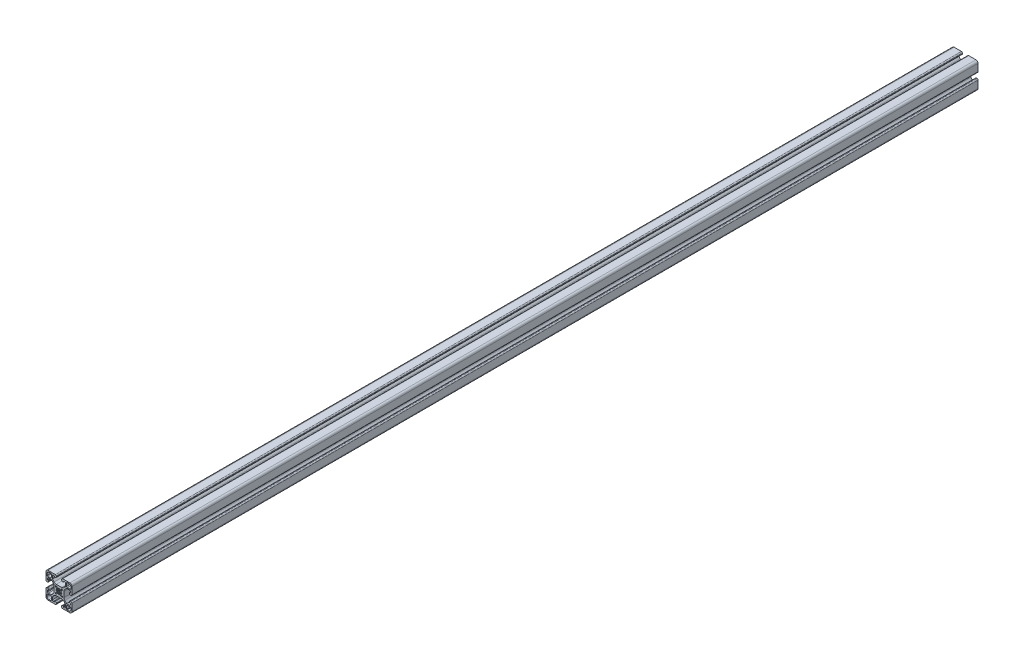
SolidWorks part; units mm, degrees
other "Extrude1"
material "6105-T5 Aluminum"
ref_plane "Front Plane" through (0, 0, 0) normal (0, 0, 1) x (1, 0, 0)
ref_plane "Top Plane" through (0, 0, 0) normal (0, 1, 0) x (1, 0, 0)
ref_plane "Right Plane" through (0, 0, 0) normal (1, 0, 0) x (0, 0, -1)
sketch "Sketch1" plane through (0, 0, 0) normal (0, 0, 1) x (1, 0, 0)
  line L0 (12.4898, -18.345) -> (15.545, -18.345)
  line L1 (11.8598, -13.1298) -> (11.8598, -17.715)
  line L2 (17.715, -11.8598) -> (13.1298, -11.8598)
  line L3 (18.345, -15.545) -> (18.345, -12.4898)
  line L4 (-18.345, -12.4898) -> (-18.345, -15.545)
  line L5 (-13.1298, -11.8598) -> (-17.715, -11.8598)
  line L6 (-11.8598, -17.715) -> (-11.8598, -13.1298)
  line L7 (-15.545, -18.345) -> (-12.4898, -18.345)
  line L8 (18.345, 12.4898) -> (18.345, 15.545)
  line L9 (13.1298, 11.8598) -> (17.715, 11.8598)
  line L10 (11.8598, 17.715) -> (11.8598, 13.1298)
  line L11 (15.545, 18.345) -> (12.4898, 18.345)
  line L12 (-12.4898, 18.345) -> (-15.545, 18.345)
  line L13 (-11.8598, 13.1298) -> (-11.8598, 17.715)
  line L14 (-17.715, 11.8598) -> (-13.1298, 11.8598)
  line L15 (-18.345, 15.545) -> (-18.345, 12.4898)
  line L16 (-5.63, 20) -> (-16.83, 20)
  line L17 (-20, 16.83) -> (-20, 5.63)
  line L18 (-18.43, 4.06) -> (-17.57, 4.06)
  line L19 (-16, 5.63) -> (-16, 6.605)
  line L20 (-16.25, 6.855) -> (-17.25, 6.855)
  line L21 (-17.5, 7.105) -> (-17.5, 9.015)
  line L22 (-16.23, 10.285) -> (-12.2162, 10.285)
  line L23 (-11.5869, 10.0243) -> (-9.0762, 7.5137)
  line L24 (-7.685, 4.1549) -> (-7.685, -4.1549)
  line L25 (-9.0762, -7.5137) -> (-11.5869, -10.0243)
  line L26 (-12.2162, -10.285) -> (-16.23, -10.285)
  line L27 (-17.5, -9.015) -> (-17.5, -7.105)
  line L28 (-17.25, -6.855) -> (-16.25, -6.855)
  line L29 (-16, -6.605) -> (-16, -5.63)
  line L30 (-17.57, -4.06) -> (-18.43, -4.06)
  line L31 (-20, -5.63) -> (-20, -16.83)
  line L32 (-16.83, -20) -> (-5.63, -20)
  line L33 (-4.06, -18.43) -> (-4.06, -17.57)
  line L34 (-5.63, -16) -> (-6.605, -16)
  line L35 (-6.855, -16.25) -> (-6.855, -17.25)
  line L36 (-7.105, -17.5) -> (-9.015, -17.5)
  line L37 (-10.285, -16.23) -> (-10.285, -12.2162)
  line L38 (-10.0243, -11.5869) -> (-7.5137, -9.0762)
  line L39 (-4.1549, -7.685) -> (4.1549, -7.685)
  line L40 (7.5137, -9.0762) -> (10.0243, -11.5869)
  line L41 (10.285, -12.2162) -> (10.285, -16.23)
  line L42 (9.015, -17.5) -> (7.105, -17.5)
  line L43 (6.855, -17.25) -> (6.855, -16.25)
  line L44 (6.605, -16) -> (5.63, -16)
  line L45 (4.06, -17.57) -> (4.06, -18.43)
  line L46 (5.63, -20) -> (16.83, -20)
  line L47 (20, -16.83) -> (20, -5.63)
  line L48 (18.43, -4.06) -> (17.57, -4.06)
  line L49 (16, -5.63) -> (16, -6.605)
  line L50 (16.25, -6.855) -> (17.25, -6.855)
  line L51 (17.5, -7.105) -> (17.5, -9.015)
  line L52 (16.23, -10.285) -> (12.2162, -10.285)
  line L53 (11.5869, -10.0243) -> (9.0762, -7.5137)
  line L54 (7.685, -4.1549) -> (7.685, 4.1549)
  line L55 (9.0762, 7.5137) -> (11.5869, 10.0243)
  line L56 (12.2162, 10.285) -> (16.23, 10.285)
  line L57 (17.5, 9.015) -> (17.5, 7.105)
  line L58 (17.25, 6.855) -> (16.25, 6.855)
  line L59 (16, 6.605) -> (16, 5.63)
  line L60 (17.57, 4.06) -> (18.43, 4.06)
  line L61 (20, 5.63) -> (20, 16.83)
  line L62 (16.83, 20) -> (5.63, 20)
  line L63 (4.06, 18.43) -> (4.06, 17.57)
  line L64 (5.63, 16) -> (6.605, 16)
  line L65 (6.855, 16.25) -> (6.855, 17.25)
  line L66 (7.105, 17.5) -> (9.015, 17.5)
  line L67 (10.285, 16.23) -> (10.285, 12.2162)
  line L68 (10.0243, 11.5869) -> (7.5137, 9.0762)
  line L69 (4.1549, 7.685) -> (-4.1549, 7.685)
  line L70 (-7.5137, 9.0762) -> (-10.0243, 11.5869)
  line L71 (-10.285, 12.2162) -> (-10.285, 16.23)
  line L72 (-9.015, 17.5) -> (-7.105, 17.5)
  line L73 (-6.855, 17.25) -> (-6.855, 16.25)
  line L74 (-6.605, 16) -> (-5.63, 16)
  line L75 (-4.06, 17.57) -> (-4.06, 18.43)
  line L76 (-4.8481, -5.4393) -> (-3.712, -5.1263)
  line L77 (-3.712, -5.1263) -> (-1.5907, -3.0049)
  line L78 (-0.625, -3.3421) -> (-0.4923, -4.0876)
  line L79 (0.4923, -4.0876) -> (0.625, -3.3421)
  line L80 (1.5907, -3.0049) -> (3.712, -5.1263)
  line L81 (3.712, -5.1263) -> (4.8481, -5.4393)
  line L82 (5.4393, -4.8481) -> (5.1263, -3.712)
  line L83 (5.1263, -3.712) -> (3.0049, -1.5907)
  line L84 (3.3421, -0.625) -> (4.0876, -0.4923)
  line L85 (4.0876, 0.4923) -> (3.3421, 0.625)
  line L86 (3.0049, 1.5907) -> (5.1263, 3.712)
  line L87 (5.1263, 3.712) -> (5.4393, 4.8481)
  line L88 (4.8481, 5.4393) -> (3.712, 5.1263)
  line L89 (3.712, 5.1263) -> (1.5907, 3.0049)
  line L90 (0.625, 3.3421) -> (0.4923, 4.0876)
  line L91 (-0.4923, 4.0876) -> (-0.625, 3.3421)
  line L92 (-1.5907, 3.0049) -> (-3.712, 5.1263)
  line L93 (-3.712, 5.1263) -> (-4.8481, 5.4393)
  line L94 (-5.4393, 4.8481) -> (-5.1263, 3.712)
  line L95 (-5.1263, 3.712) -> (-3.0049, 1.5907)
  line L96 (-3.3421, 0.625) -> (-4.0876, 0.4923)
  line L97 (-4.0876, -0.4923) -> (-3.3421, -0.625)
  line L98 (-3.0049, -1.5907) -> (-5.1263, -3.712)
  line L99 (-5.1263, -3.712) -> (-5.4393, -4.8481)
  arc A0 (15.545, -18.345) -> (18.345, -15.545) centre (15.545, -15.545) ccw
  arc A1 (11.8598, -17.715) -> (12.4898, -18.345) centre (12.4898, -17.715) ccw
  arc A2 (13.1298, -11.8598) -> (11.8598, -13.1298) centre (13.1298, -13.1298) ccw
  arc A3 (18.345, -12.4898) -> (17.715, -11.8598) centre (17.715, -12.4898) ccw
  arc A4 (-18.345, -15.545) -> (-15.545, -18.345) centre (-15.545, -15.545) ccw
  arc A5 (-17.715, -11.8598) -> (-18.345, -12.4898) centre (-17.715, -12.4898) ccw
  arc A6 (-11.8598, -13.1298) -> (-13.1298, -11.8598) centre (-13.1298, -13.1298) ccw
  arc A7 (-12.4898, -18.345) -> (-11.8598, -17.715) centre (-12.4898, -17.715) ccw
  arc A8 (18.345, 15.545) -> (15.545, 18.345) centre (15.545, 15.545) ccw
  arc A9 (17.715, 11.8598) -> (18.345, 12.4898) centre (17.715, 12.4898) ccw
  arc A10 (11.8598, 13.1298) -> (13.1298, 11.8598) centre (13.1298, 13.1298) ccw
  arc A11 (12.4898, 18.345) -> (11.8598, 17.715) centre (12.4898, 17.715) ccw
  arc A12 (-15.545, 18.345) -> (-18.345, 15.545) centre (-15.545, 15.545) ccw
  arc A13 (-11.8598, 17.715) -> (-12.4898, 18.345) centre (-12.4898, 17.715) ccw
  arc A14 (-13.1298, 11.8598) -> (-11.8598, 13.1298) centre (-13.1298, 13.1298) ccw
  arc A15 (-18.345, 12.4898) -> (-17.715, 11.8598) centre (-17.715, 12.4898) ccw
  arc A16 (-4.06, 18.43) -> (-5.63, 20) centre (-5.63, 18.43) ccw
  arc A17 (-16.83, 20) -> (-20, 16.83) centre (-16.83, 16.83) ccw
  arc A18 (-20, 5.63) -> (-18.43, 4.06) centre (-18.43, 5.63) ccw
  arc A19 (-17.57, 4.06) -> (-16, 5.63) centre (-17.57, 5.63) ccw
  arc A20 (-16, 6.605) -> (-16.25, 6.855) centre (-16.25, 6.605) ccw
  arc A21 (-17.5, 7.105) -> (-17.25, 6.855) centre (-17.25, 7.105) ccw
  arc A22 (-16.23, 10.285) -> (-17.5, 9.015) centre (-16.23, 9.015) ccw
  arc A23 (-11.5869, 10.0243) -> (-12.2162, 10.285) centre (-12.2162, 9.395) ccw
  arc A24 (-7.685, 4.1549) -> (-9.0762, 7.5137) centre (-12.435, 4.1549) ccw
  arc A25 (-9.0762, -7.5137) -> (-7.685, -4.1549) centre (-12.435, -4.1549) ccw
  arc A26 (-12.2162, -10.285) -> (-11.5869, -10.0243) centre (-12.2162, -9.395) ccw
  arc A27 (-17.5, -9.015) -> (-16.23, -10.285) centre (-16.23, -9.015) ccw
  arc A28 (-17.25, -6.855) -> (-17.5, -7.105) centre (-17.25, -7.105) ccw
  arc A29 (-16.25, -6.855) -> (-16, -6.605) centre (-16.25, -6.605) ccw
  arc A30 (-16, -5.63) -> (-17.57, -4.06) centre (-17.57, -5.63) ccw
  arc A31 (-18.43, -4.06) -> (-20, -5.63) centre (-18.43, -5.63) ccw
  arc A32 (-20, -16.83) -> (-16.83, -20) centre (-16.83, -16.83) ccw
  arc A33 (-5.63, -20) -> (-4.06, -18.43) centre (-5.63, -18.43) ccw
  arc A34 (-4.06, -17.57) -> (-5.63, -16) centre (-5.63, -17.57) ccw
  arc A35 (-6.605, -16) -> (-6.855, -16.25) centre (-6.605, -16.25) ccw
  arc A36 (-7.105, -17.5) -> (-6.855, -17.25) centre (-7.105, -17.25) ccw
  arc A37 (-10.285, -16.23) -> (-9.015, -17.5) centre (-9.015, -16.23) ccw
  arc A38 (-10.0243, -11.5869) -> (-10.285, -12.2162) centre (-9.395, -12.2162) ccw
  arc A39 (-4.1549, -7.685) -> (-7.5137, -9.0762) centre (-4.1549, -12.435) ccw
  arc A40 (7.5137, -9.0762) -> (4.1549, -7.685) centre (4.1549, -12.435) ccw
  arc A41 (10.285, -12.2162) -> (10.0243, -11.5869) centre (9.395, -12.2162) ccw
  arc A42 (9.015, -17.5) -> (10.285, -16.23) centre (9.015, -16.23) ccw
  arc A43 (6.855, -17.25) -> (7.105, -17.5) centre (7.105, -17.25) ccw
  arc A44 (6.855, -16.25) -> (6.605, -16) centre (6.605, -16.25) ccw
  arc A45 (5.63, -16) -> (4.06, -17.57) centre (5.63, -17.57) ccw
  arc A46 (4.06, -18.43) -> (5.63, -20) centre (5.63, -18.43) ccw
  arc A47 (16.83, -20) -> (20, -16.83) centre (16.83, -16.83) ccw
  arc A48 (20, -5.63) -> (18.43, -4.06) centre (18.43, -5.63) ccw
  arc A49 (17.57, -4.06) -> (16, -5.63) centre (17.57, -5.63) ccw
  arc A50 (16, -6.605) -> (16.25, -6.855) centre (16.25, -6.605) ccw
  arc A51 (17.5, -7.105) -> (17.25, -6.855) centre (17.25, -7.105) ccw
  arc A52 (16.23, -10.285) -> (17.5, -9.015) centre (16.23, -9.015) ccw
  arc A53 (11.5869, -10.0243) -> (12.2162, -10.285) centre (12.2162, -9.395) ccw
  arc A54 (7.685, -4.1549) -> (9.0762, -7.5137) centre (12.435, -4.1549) ccw
  arc A55 (9.0762, 7.5137) -> (7.685, 4.1549) centre (12.435, 4.1549) ccw
  arc A56 (12.2162, 10.285) -> (11.5869, 10.0243) centre (12.2162, 9.395) ccw
  arc A57 (17.5, 9.015) -> (16.23, 10.285) centre (16.23, 9.015) ccw
  arc A58 (17.25, 6.855) -> (17.5, 7.105) centre (17.25, 7.105) ccw
  arc A59 (16.25, 6.855) -> (16, 6.605) centre (16.25, 6.605) ccw
  arc A60 (16, 5.63) -> (17.57, 4.06) centre (17.57, 5.63) ccw
  arc A61 (18.43, 4.06) -> (20, 5.63) centre (18.43, 5.63) ccw
  arc A62 (20, 16.83) -> (16.83, 20) centre (16.83, 16.83) ccw
  arc A63 (5.63, 20) -> (4.06, 18.43) centre (5.63, 18.43) ccw
  arc A64 (4.06, 17.57) -> (5.63, 16) centre (5.63, 17.57) ccw
  arc A65 (6.605, 16) -> (6.855, 16.25) centre (6.605, 16.25) ccw
  arc A66 (7.105, 17.5) -> (6.855, 17.25) centre (7.105, 17.25) ccw
  arc A67 (10.285, 16.23) -> (9.015, 17.5) centre (9.015, 16.23) ccw
  arc A68 (10.0243, 11.5869) -> (10.285, 12.2162) centre (9.395, 12.2162) ccw
  arc A69 (4.1549, 7.685) -> (7.5137, 9.0762) centre (4.1549, 12.435) ccw
  arc A70 (-7.5137, 9.0762) -> (-4.1549, 7.685) centre (-4.1549, 12.435) ccw
  arc A71 (-10.285, 12.2162) -> (-10.0243, 11.5869) centre (-9.395, 12.2162) ccw
  arc A72 (-9.015, 17.5) -> (-10.285, 16.23) centre (-9.015, 16.23) ccw
  arc A73 (-6.855, 17.25) -> (-7.105, 17.5) centre (-7.105, 17.25) ccw
  arc A74 (-6.855, 16.25) -> (-6.605, 16) centre (-6.605, 16.25) ccw
  arc A75 (-5.63, 16) -> (-4.06, 17.57) centre (-5.63, 17.57) ccw
  arc A76 (-1.5907, -3.0049) -> (-0.625, -3.3421) centre (0, 0) ccw
  arc A77 (-0.4923, -4.0876) -> (0.4923, -4.0876) centre (0, -4) ccw
  arc A78 (0.625, -3.3421) -> (1.5907, -3.0049) centre (0, 0) ccw
  arc A79 (4.8481, -5.4393) -> (5.4393, -4.8481) centre (4.9497, -4.9497) ccw
  arc A80 (3.0049, -1.5907) -> (3.3421, -0.625) centre (0, 0) ccw
  arc A81 (4.0876, -0.4923) -> (4.0876, 0.4923) centre (4, 0) ccw
  arc A82 (3.3421, 0.625) -> (3.0049, 1.5907) centre (0, 0) ccw
  arc A83 (5.4393, 4.8481) -> (4.8481, 5.4393) centre (4.9497, 4.9497) ccw
  arc A84 (1.5907, 3.0049) -> (0.625, 3.3421) centre (0, 0) ccw
  arc A85 (0.4923, 4.0876) -> (-0.4923, 4.0876) centre (0, 4) ccw
  arc A86 (-0.625, 3.3421) -> (-1.5907, 3.0049) centre (0, 0) ccw
  arc A87 (-4.8481, 5.4393) -> (-5.4393, 4.8481) centre (-4.9497, 4.9497) ccw
  arc A88 (-3.0049, 1.5907) -> (-3.3421, 0.625) centre (0, 0) ccw
  arc A89 (-4.0876, 0.4923) -> (-4.0876, -0.4923) centre (-4, 0) ccw
  arc A90 (-3.3421, -0.625) -> (-3.0049, -1.5907) centre (0, 0) ccw
  arc A91 (-5.4393, -4.8481) -> (-4.8481, -5.4393) centre (-4.9497, -4.9497) ccw
extrude "Extrude1" add sketch "Sketch1" against normal blind 1400
